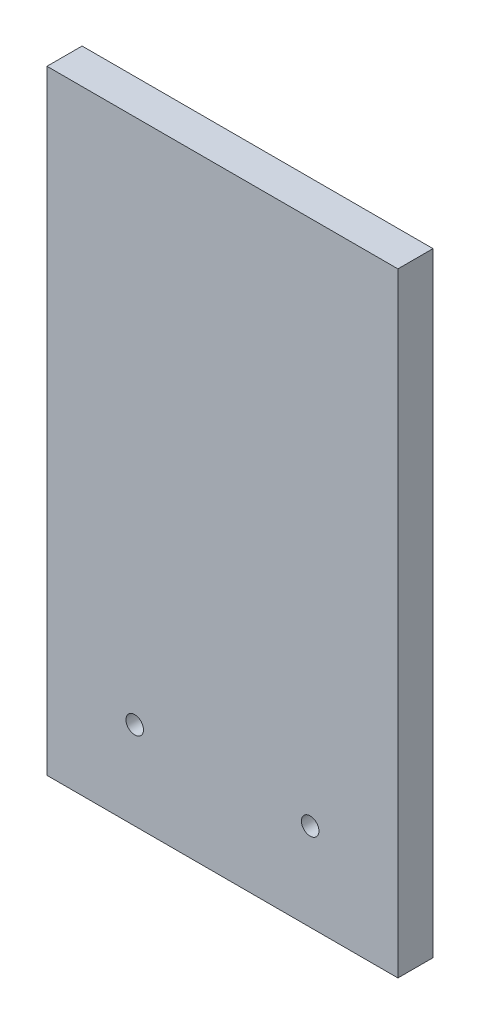
SolidWorks part; units mm, degrees
ref_plane "Plano frontal" through (0, 0, 0) normal (0, 0, 1) x (1, 0, 0)
ref_plane "Plano superior" through (0, 0, 0) normal (0, 1, 0) x (1, 0, 0)
ref_plane "Plano direito" through (0, 0, 0) normal (1, 0, 0) x (0, 0, -1)
sketch "Esboço1" plane through (0, 0, 0) normal (0, 0, 1) x (1, 0, 0)
  line L1 (95.8436, 73.8592) -> (85.8436, 73.8592)
  line L2 (95.8436, 73.8592) -> (95.8436, 56.3592)
  line L3 (95.8436, 56.3592) -> (85.8436, 56.3592)
  line L4 (85.8436, 73.8592) -> (85.8436, 56.3592)
  dimension "D1" = 10
  dimension "D2" = 17.5
extrude "Ressalto-extrusão1" add sketch "Esboço1" along normal blind 1
sketch "Esboço2" plane through (0, 0, 1) normal (0, 0, 1) x (1, 0, 0)
  line L0 (85.8436, 73.8592) -> (90.8436, 73.8592) construction
  line L1 (95.8436, 73.8592) -> (85.8436, 73.8592) construction
  line L2 (90.8436, 73.8592) -> (95.8436, 73.8592) construction
  line L3 (88.3436, 73.8592) -> (88.3436, 58.8592) construction
  line L4 (88.3436, 58.8592) -> (93.3436, 58.8592) construction
  line L5 (93.3436, 58.8592) -> (93.3436, 73.8592) construction
  circle A0 centre (88.3436, 58.8592) radius 0.25
  circle A1 centre (93.3436, 58.8592) radius 0.25
  dimension "D1" = 0.5
  dimension "D2" = 15
extrude "Corte-extrusão1" cut sketch "Esboço2" against normal through all contours A0 | A1
